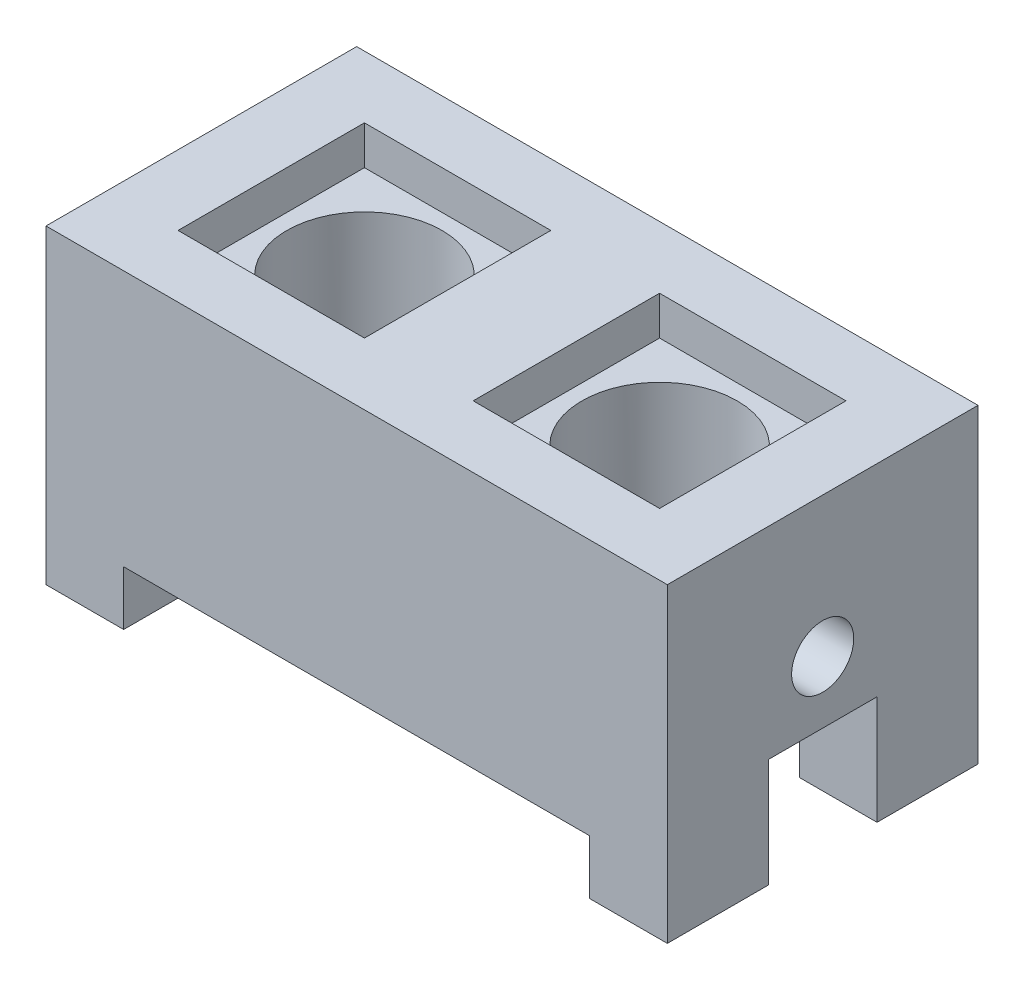
SolidWorks part; units mm, degrees
ref_plane "Front Plane" through (0, 0, 0) normal (0, 0, 1) x (1, 0, 0)
ref_plane "Top Plane" through (0, 0, 0) normal (0, 1, 0) x (1, 0, 0)
ref_plane "Right Plane" through (0, 0, 0) normal (1, 0, 0) x (0, 0, -1)
sketch "Sketch1" plane through (0, 0, 0) normal (0, 0, 1) x (1, 0, 0)
  line L1 (0, 0) -> (80, 0)
  line L2 (0, 0) -> (0, 40)
  line L3 (0, 40) -> (80, 40)
  line L4 (80, 0) -> (80, 40)
  dimension "D1" = 80
  dimension "D2" = 40
extrude "Boss-Extrude1" add sketch "Sketch1" along normal mid plane 40
sketch "Sketch2" plane through (0, 0, 20) normal (0, 0, 1) x (1, 0, 0)
  line L0 (10, 0) -> (10, 7)
  line L1 (0, 0) -> (80, 0) construction
  line L2 (10, 7) -> (70, 7)
  line L3 (70, 7) -> (70, 0)
  line L4 (70, 0) -> (10, 0)
  dimension "D1" = 7
  dimension "D2" = 10
  dimension "D3" = 10
extrude "Cut-Extrude1" cut sketch "Sketch2" against normal blind 40
sketch "Sketch3" plane through (80, 0, 0) normal (1, 0, 0) x (0, 0, -1)
  line L0 (-7, 0) -> (-7, 14)
  line L1 (-20, 0) -> (20, 0) construction
  line L2 (-7, 14) -> (7, 14)
  line L3 (7, 14) -> (7, 0)
  line L4 (7, 0) -> (-7, 0)
  dimension "D1" = 13
  dimension "D2" = 13
  dimension "D3" = 14
extrude "Cut-Extrude2" cut sketch "Sketch3" against normal blind 80
sketch "Sketch4" plane through (80, 0, 0) normal (1, 0, 0) x (0, 0, -1)
  circle A0 centre (0, 22) radius 4
  dimension "D1" = 8
  dimension "D2" = 22
extrude "Cut-Extrude3" cut sketch "Sketch4" against normal blind 80 and the other way through all
sketch "Sketch5" plane through (0, 40, 0) normal (0, 1, 0) x (1, 0, 0)
  line L0 (47, 12) -> (71, 12)
  line L1 (71, 12) -> (71, -12)
  line L2 (71, -12) -> (47, -12)
  line L3 (47, -12) -> (47, 12)
  line L4 (9, 12) -> (33, 12)
  line L5 (33, 12) -> (33, -12)
  line L6 (33, -12) -> (9, -12)
  line L7 (9, -12) -> (9, 12)
  line L8 (0, -20) -> (0, 20) construction
  line L10 (80, -20) -> (0, -20) construction
  point P14 (9, 0)
  dimension "D1" = 24
  dimension "D2" = 24
  dimension "D3" = 24
  dimension "D4" = 24
  dimension "D5" = 9
  dimension "D6" = 14
  dimension "D7" = 8
extrude "Cut-Extrude4" cut sketch "Sketch5" against normal blind 5
sketch "Sketch6" plane through (0, 40, 0) normal (0, 1, 0) x (1, 0, 0)
  line L0 (47, 12) -> (47, -12) construction
  line L3 (33, -12) -> (33, 12) construction
  circle A0 centre (59, 0) radius 10
  circle A1 centre (21, 0) radius 10
  point P4 (0, 0)
  point P5 (0, 0)
  point P8 (0, 0)
  point P9 (0, 0)
  point P10 (0, 0)
  point P16 (0, 0)
  point P17 (0, 0)
  dimension "D1" = 20
  dimension "D2" = 20
  dimension "D3" = 12
  dimension "D4" = 12
extrude "Cut-Extrude6" cut sketch "Sketch6" against normal through all
